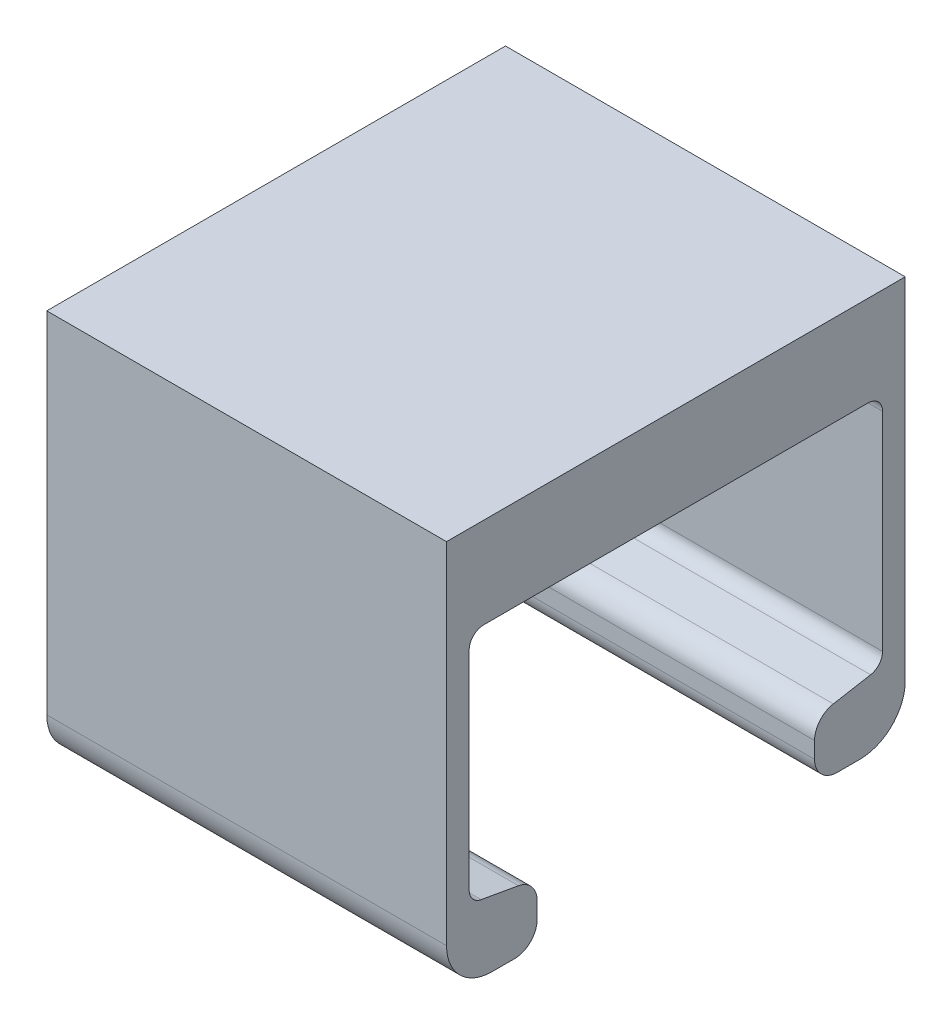
SolidWorks part; units mm, degrees
ref_plane "Front Plane" through (0, 0, 0) normal (0, 0, 1) x (1, 0, 0)
ref_plane "Top Plane" through (0, 0, 0) normal (0, 1, 0) x (1, 0, 0)
ref_plane "Right Plane" through (0, 0, 0) normal (1, 0, 0) x (0, 0, -1)
sketch "Sketch1" plane through (0, 0, 0) normal (1, 0, 0) x (0, 0, -1)
  line L1 (-16.0655, -10.3253) -> (-9.7155, -10.3253)
  line L2 (-9.7155, -6.2638) -> (-9.7155, -10.3253)
  line L3 (0, 17.358) -> (0, 11.008) construction
  line L4 (-14.5247, -5.4158) -> (-14.478, -5.4241) construction
  line L5 (0, 11.008) -> (14.478, 11.008)
  line L6 (14.478, -5.4241) -> (14.478, 11.008)
  line L7 (9.7155, -6.2638) -> (14.478, -5.4241)
  line L8 (9.7155, -6.2638) -> (9.7155, -10.3253)
  line L9 (16.0655, -10.3253) -> (9.7155, -10.3253)
  line L10 (16.0655, 17.358) -> (16.0655, -10.3253)
  line L11 (0, 17.358) -> (16.0655, 17.358)
  line L12 (-16.0655, 17.358) -> (-16.0655, -10.3253)
  line L14 (0, 17.358) -> (-20.828, 17.358) construction
  line L16 (0, 11.008) -> (-14.478, 11.008)
  line L20 (-9.7155, -6.2638) -> (-14.478, -5.4241)
  line L22 (-14.478, -5.4241) -> (-14.478, 11.008)
  line L23 (-19.5, 11.008) -> (19.5, 11.008) construction
  line L24 (0, 17.358) -> (-16.0655, 17.358)
  line L27 (-20.828, -4.6471) -> (-20.828, -4.6471) construction
  line L28 (-20.828, -4.6471) -> (-20.828, 17.358) construction
  dimension "D4" = 10.3253
  dimension "D5" = 100
  dimension "D6" = 4.0615
  dimension "D7" = 1.5875
  dimension "D8" = 1.5875
  dimension "D9" = 10.3253
  dimension "D10" = 28.956
  dimension "D2" = 6.35
  dimension "D3" = 6.35
extrude "Boss-Extrude1" add sketch "Sketch1" along normal up to vertex (14 mm away) and the other way up to vertex (14 mm away)
fillet "Fillet2" radius 3.175 2 edges at (0, -10.3253, -16.0655) (0, -10.3253, 16.0655)
fillet "Fillet3" radius 1.016 4 edges at (0, -5.4241, 14.478) (0, -5.4241, -14.478) (0, 11.008, 14.478) (0, 11.008, -14.478)
fillet "Fillet4" radius 1.5875 4 edges at (0, -10.3253, -9.7155) (0, -10.3253, 9.7155) (0, -6.2638, 9.7155) (0, -6.2638, -9.7155)
sketch "Sketch3" plane through (0, 11.008, 0) normal (0, -1, 0) x (-1, 0, 0)
  circle A0 centre (0, 0) radius 9.0297
  point P2 (0, 0)
  point P3 (0, 0)
  point P5 (0, 0)
  dimension "D1" = 18.0594
extrude "Cut-Extrude1" cut sketch "Sketch3" against normal blind 3.048
